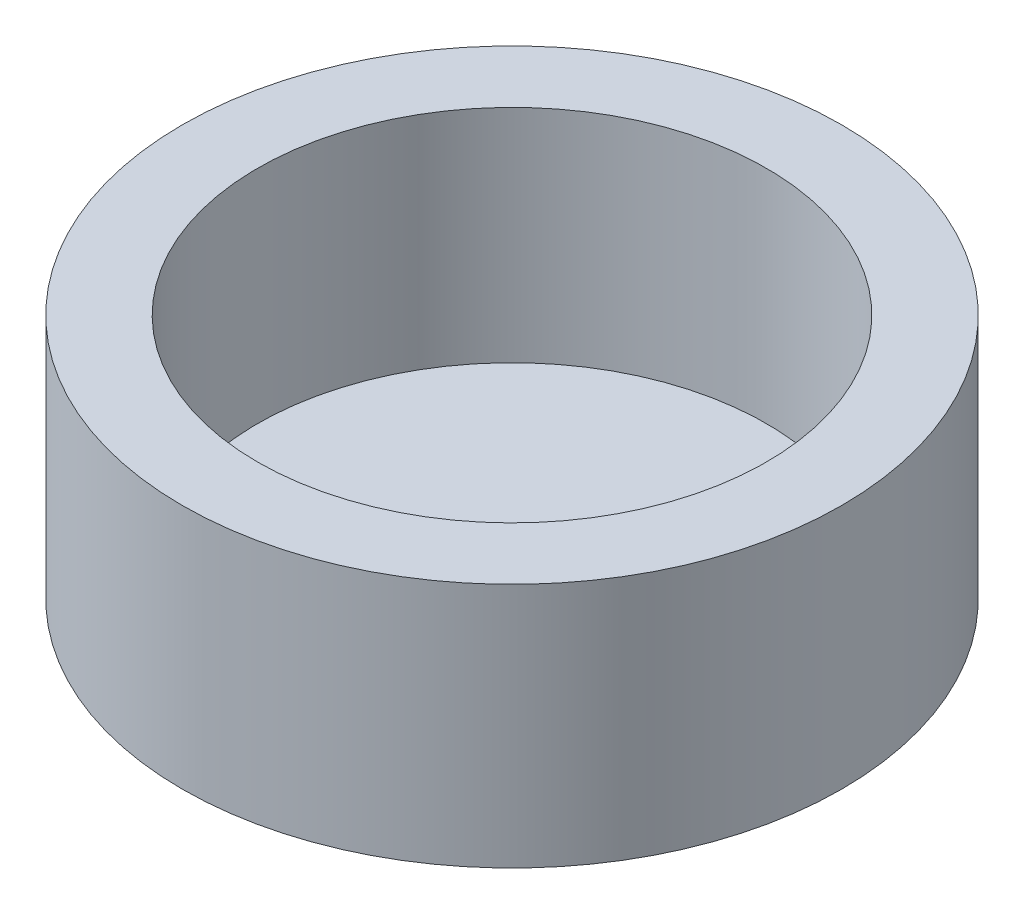
SolidWorks part; units mm, degrees
ref_plane "Front Plane" through (0, 0, 0) normal (0, 0, 1) x (1, 0, 0)
ref_plane "Top Plane" through (0, 0, 0) normal (0, 1, 0) x (1, 0, 0)
ref_plane "Right Plane" through (0, 0, 0) normal (1, 0, 0) x (0, 0, -1)
sketch "Sketch1" plane through (0, 0, 0) normal (0, 1, 0) x (1, 0, 0)
  circle A0 centre (0, 0) radius 26.8366
extrude "DC Motor Cavity Base" add sketch "Sketch1" along normal blind 20
sketch "Sketch2" plane through (0, 20, 0) normal (0, 1, 0) x (1, 0, 0)
  circle A0 centre (0, 0) radius 20.7116
extrude "Cavity" cut sketch "Sketch2" against normal blind 18
